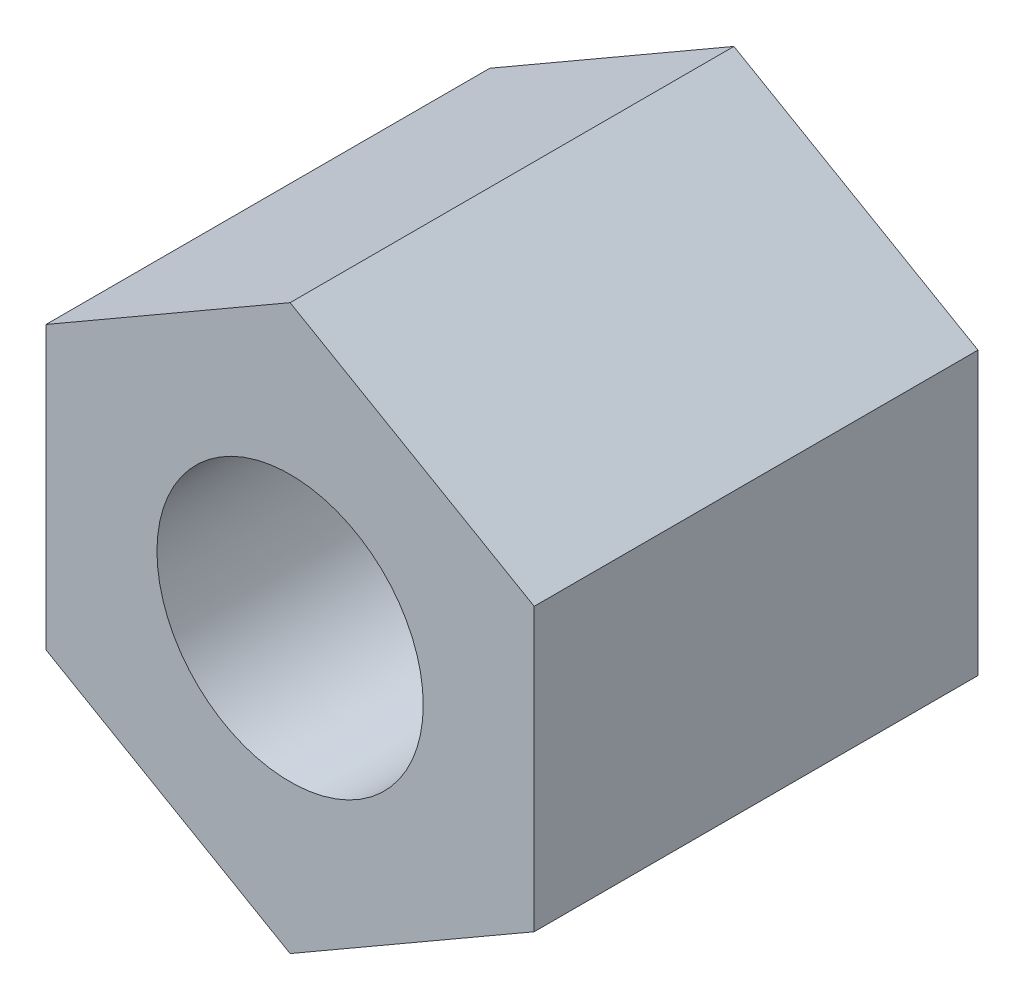
SolidWorks part; units mm, degrees
material "Messing"
ref_plane "Ebene vorne" through (0, 0, 0) normal (1, 0, 0) x (0, 1, 0)
ref_plane "Ebene oben" through (0, 0, 0) normal (0, 0, 1) x (0, 1, 0)
ref_plane "Ebene rechts" through (0, 0, 0) normal (0, 1, 0) x (-1, 0, 0)
sketch "Skizze1" plane through (0, 0, 0) normal (0, 0, 1) x (0, 1, 0)
  line L7 (3.1754, 0) -> (1.5877, 2.75)
  line L8 (1.5877, 2.75) -> (-1.5877, 2.75)
  line L9 (-1.5877, 2.75) -> (-3.1754, 0)
  line L10 (-3.1754, 0) -> (-1.5877, -2.75)
  line L11 (-1.5877, -2.75) -> (1.5877, -2.75)
  line L12 (1.5877, -2.75) -> (3.1754, 0)
  circle A3 centre (0, 0) radius 2.75 construction
extrude "Aufsatz-Linear austragen1" add sketch "Skizze1" along normal blind 5
sketch "Skizze2" plane through (0, 0, 5) normal (0, 0, 1) x (1, 0, 0)
  circle A0 centre (0, 0) radius 1.5
extrude "Schnitt-Linear austragen1" cut sketch "Skizze2" against normal blind 5
